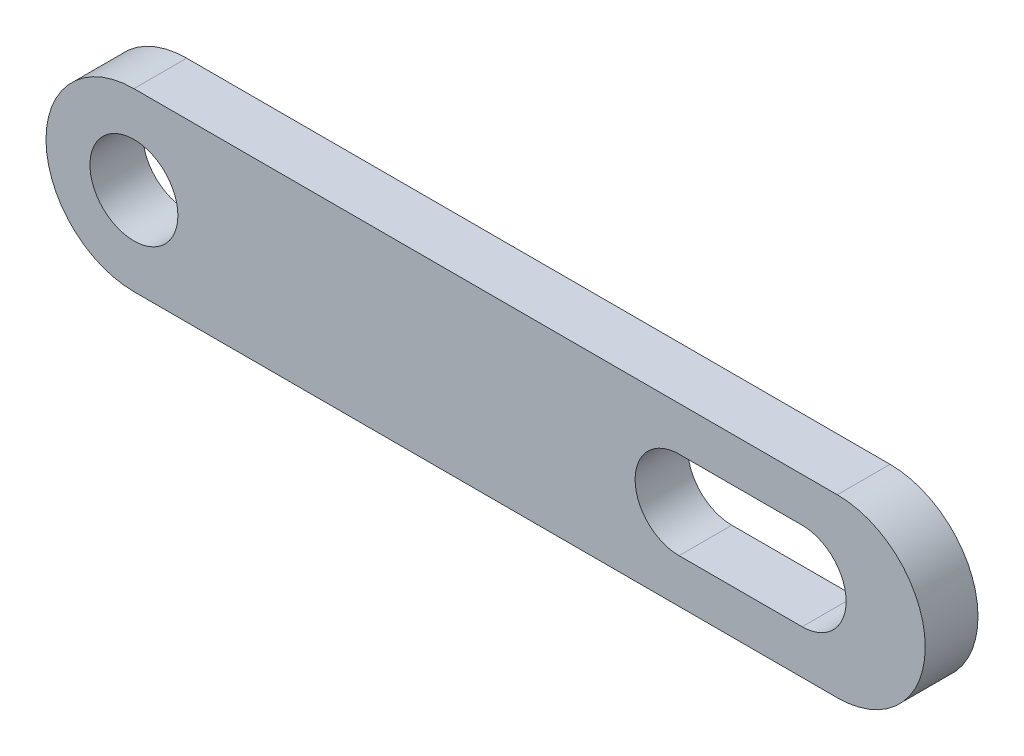
SolidWorks part; units mm, degrees
ref_plane "Front Plane" through (0, 0, 0) normal (0, 0, 1) x (1, 0, 0)
ref_plane "Top Plane" through (0, 0, 0) normal (0, 1, 0) x (1, 0, 0)
ref_plane "Right Plane" through (0, 0, 0) normal (1, 0, 0) x (0, 0, -1)
sketch "Sketch2" plane through (0, 0, 0) normal (0, 0, 1) x (1, 0, 0)
  line L0 (-20, 0) -> (20, 0) construction
  line L1 (-20, 5) -> (20, 5)
  line L2 (-20, -5) -> (20, -5)
  arc A0 (-20, 5) -> (-20, -5) centre (-20, 0) ccw
  arc A1 (20, -5) -> (20, 5) centre (20, 0) ccw
  point P2 (0, 0)
  dimension "D1" = 10
  dimension "D2" = 40
extrude "Boss-Extrude1" add sketch "Sketch2" along normal blind 3
sketch "Sketch4" plane through (0, 0, 3) normal (0, 0, 1) x (1, 0, 0)
  line L0 (11, 0) -> (18, 0) construction
  line L1 (11, 2.5) -> (18, 2.5)
  line L2 (11, -2.5) -> (18, -2.5)
  line L3 (-20, 0) -> (-20, 5) construction
  arc A0 (11, 2.5) -> (11, -2.5) centre (11, 0) ccw
  arc A1 (18, -2.5) -> (18, 2.5) centre (18, 0) ccw
  circle A2 centre (-20, 0) radius 2.5
  point P2 (14.5, 0)
  dimension "D4" = 5
  dimension "D1" = 5
  dimension "D2" = 31
  dimension "D3" = 38
extrude "Cut-Extrude1" cut sketch "Sketch4" against normal up to next
